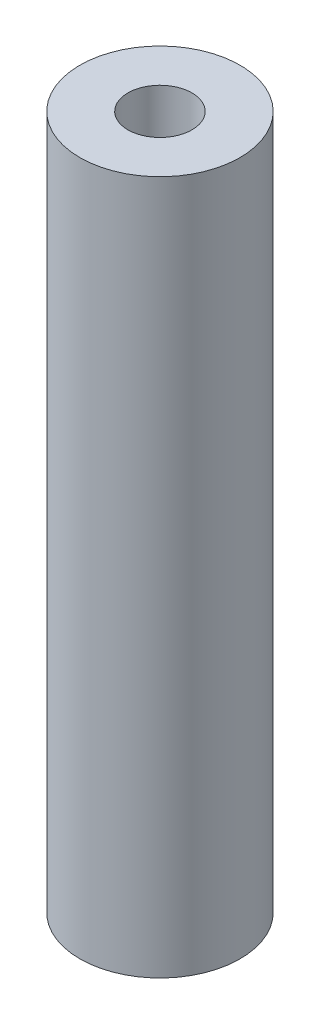
SolidWorks part; units mm, degrees
ref_plane "Alzado" through (0, 0, 0) normal (0, 0, 1) x (1, 0, 0)
ref_plane "Planta" through (0, 0, 0) normal (0, 1, 0) x (1, 0, 0)
ref_plane "Vista lateral" through (0, 0, 0) normal (1, 0, 0) x (0, 0, -1)
sketch "Croquis1" plane through (0, 0, 0) normal (0, 1, 0) x (1, 0, 0)
  circle A0 centre (0, 0) radius 7.5
  circle A1 centre (0, 0) radius 3
  dimension "D1" = 15
  dimension "D2" = 6
extrude "Saliente-Extruir1" add sketch "Croquis1" along normal blind 65
